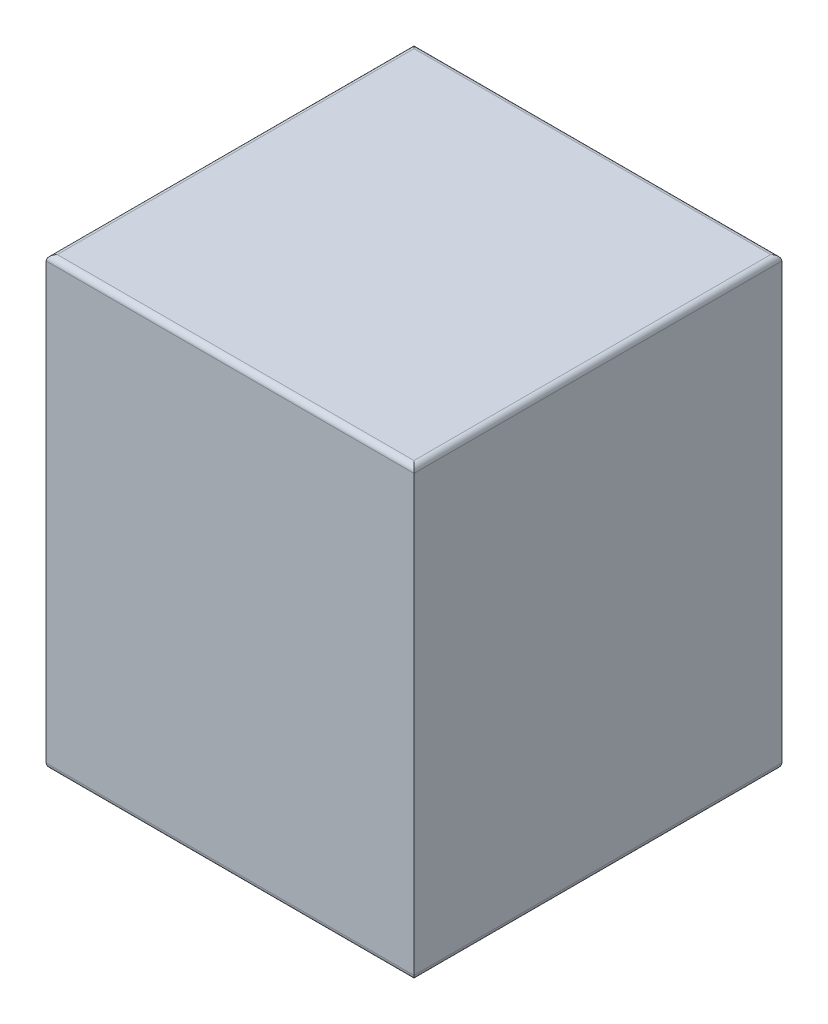
SolidWorks part; units mm, degrees
ref_plane "Front Plane" through (0, 0, 0) normal (1, 0, 0) x (0, 1, 0)
ref_plane "Top Plane" through (0, 0, 0) normal (0, 0, 1) x (0, 1, 0)
ref_plane "Right Plane" through (0, 0, 0) normal (0, 1, 0) x (-1, 0, 0)
sketch "Sketch1" plane through (0, 0, 0) normal (0, 1, 0) x (-1, 0, 0)
  line L0 (16.5, -16.5) -> (-16.5, -16.5)
  line L1 (-16.5, -16.5) -> (-16.5, 16.5)
  line L2 (-16.5, 16.5) -> (16.5, 16.5)
  line L3 (16.5, 16.5) -> (16.5, -16.5)
extrude "Boss-Extrude1" add sketch "Sketch1" along normal blind 40
fillet "Fillet1" radius 0.5 8 edges at (-16.5, 0, 0) (0, 0, 16.5) (16.5, 0, 0) (0, 0, -16.5) (-16.5, 40, 0) (0, 40, 16.5) (16.5, 40, 0) (0, 40, -16.5)
